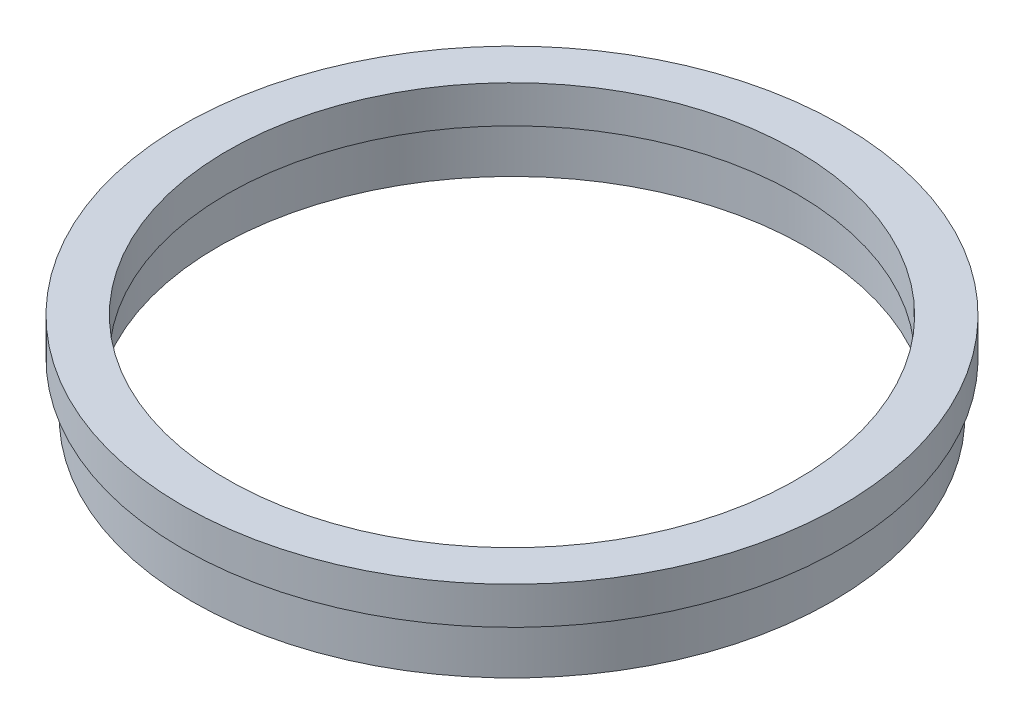
SolidWorks part; units mm, degrees
ref_plane "前视基准面" through (0, 0, 0) normal (0, 0, 1) x (1, 0, 0)
ref_plane "上视基准面" through (0, 0, 0) normal (0, 1, 0) x (1, 0, 0)
ref_plane "右视基准面" through (0, 0, 0) normal (1, 0, 0) x (0, 0, -1)
other "Configuration Table"
sketch "草图1" plane through (0, 0, 0) normal (0, 1, 0) x (1, 0, 0)
  circle A8 centre (0, 0) radius 32.9
  dimension "D1" = 65.8
extrude "拉伸-薄壁1" add sketch "草图1" along normal blind 5.4 thin thin type two direction wall 1.5 second wall 1.5
sketch "草图2" plane through (0, 5.4, 0) normal (0, 1, 0) x (1, 0, 0)
  circle A0 centre (0, 0) radius 35.4
  circle A1 centre (0, 0) radius 34.4 construction
  circle A2 centre (0, 0) radius 30.4
  circle A3 centre (0, 0) radius 31.4 construction
  dimension "D1" = 1
  dimension "D2" = 1
extrude "凸台-拉伸1" add sketch "草图2" along normal blind 4
sketch "草图3" plane through (0, 0, 0) normal (0, -1, 0) x (1, 0, 0)
  line L0 (0, 34.4) -> (0, 31.4)
  circle A0 centre (0, 32.9) radius 0.5
  circle A1 centre (0, 0) radius 34.4 construction
  circle A2 centre (0, 0) radius 31.4 construction
  dimension "D1" = 1
extrude "切除-拉伸1" cut sketch "草图3" against normal blind 3 contours A0
pattern_circular "阵列(圆周)1" count 6 over 360 about axis through (0, 0, 0) along (0, 1, 0) of "切除-拉伸1"
sketch "草图4" plane through (0, 0, 0) normal (0, -1, 0) x (1, 0, 0)
  circle A0 centre (0, 0) radius 34.3
  circle A1 centre (0, 0) radius 31.5
  circle A2 centre (0, 0) radius 34.4 construction
  circle A3 centre (0, 0) radius 31.4 construction
  point P4 (0, 0)
  dimension "D1" = 0.1
  dimension "D2" = 0.1
extrude "切除-拉伸2" cut sketch "草图4" against normal up to surface (5.4 mm away) flip side to cut up to face at (34.4, 5.4, 0)
sketch "草图5" plane through (0, 0, 0) normal (0, -1, 0) x (1, 0, 0)
  circle A0 centre (0, 0) radius 35.3
  circle A1 centre (0, 0) radius 30.5
  circle A2 centre (0, 0) radius 35.4 construction
  circle A3 centre (0, 0) radius 30.4 construction
  dimension "D1" = 0.1
  dimension "D2" = 0.1
extrude "切除-拉伸3" cut sketch "草图5" against normal through all flip side to cut
